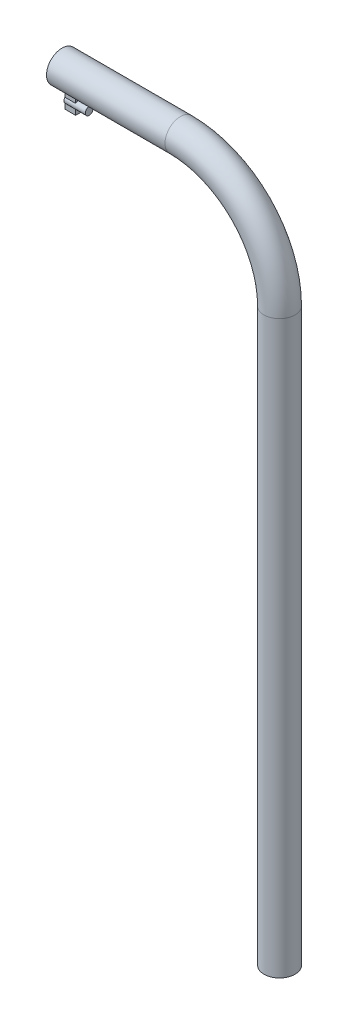
SolidWorks part; units mm, degrees
material "Chrome Stainless Steel"
ref_plane "Front Plane" through (0, 0, 0) normal (0, 0, 1) x (1, 0, 0)
ref_plane "Top Plane" through (0, 0, 0) normal (0, 1, 0) x (1, 0, 0)
ref_plane "Right Plane" through (0, 0, 0) normal (1, 0, 0) x (0, 0, -1)
sketch "Sketch1" plane through (0, 0, 0) normal (0, 1, 0) x (1, 0, 0)
  circle A0 centre (0, 0) radius 8
  dimension "D1" = 16
extrude "Boss-Extrude1" add sketch "Sketch1" along normal blind 294 from offset 169
sketch "Sketch2" plane through (0, 0, 0) normal (0, 0, 1) x (1, 0, 0)
  line L0 (-51, 176) -> (-112, 176)
  arc A0 (0, 125) -> (-51, 176) centre (-51, 125) ccw
  dimension "D3" = 51
  dimension "D1" = 51
  dimension "D2" = 125
  dimension "D4" = 61
ref_plane "Plane1" through (0, 125, 0) normal (0, 1, 0) x (1, 0, 0)
sketch "Sketch3" plane through (0, 125, 0) normal (0, 1, 0) x (1, 0, 0)
  circle A0 centre (0, 0) radius 8
  dimension "D1" = 16
sweep "Sweep1" add profiles "Sketch3" path "Sketch2"
sketch "Sketch4" plane through (0, 0, 0) normal (0, 1, 0) x (1, 0, 0)
  line L0 (-109, -1.5) -> (-103.5, -1.5)
  line L1 (-103.5, -1.5) -> (-103.5, 1.5)
  line L2 (-103.5, 1.5) -> (-109, 1.5)
  line L3 (-109, 1.5) -> (-109, -1.5)
  dimension "D1" = 5.5
  dimension "D2" = 3
  dimension "D3" = 109
  dimension "D4" = 1.5
extrude "Boss-Extrude2" add sketch "Sketch4" along normal blind 13 from offset 159
sketch "Sketch5" plane through (0, 0, 0) normal (0, 0, 1) x (1, 0, 0)
  line L0 (-109, 163) -> (-98, 163) construction
  line L1 (-109, 163) -> (-98, 163)
  line L2 (-98, 163) -> (-98, 165)
  line L3 (-98, 165) -> (-109, 165)
  line L4 (-109, 165) -> (-109, 163)
  dimension "D1" = 11
  dimension "D2" = 2
  dimension "D3" = 109
  dimension "D4" = 163
revolve "Revolve1" add sketch "Sketch5" angle 360 about L0
